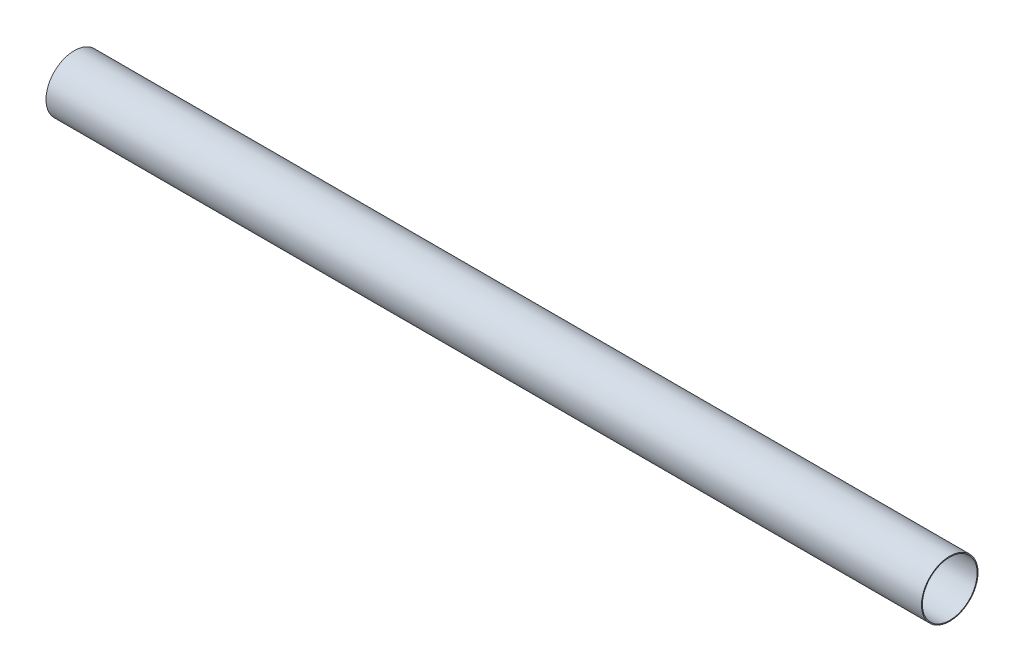
SolidWorks part; units mm, degrees
ref_plane "Front Plane" through (0, 0, 0) normal (0, 0, 1) x (1, 0, 0)
ref_plane "Top Plane" through (0, 0, 0) normal (0, 1, 0) x (1, 0, 0)
ref_plane "Right Plane" through (0, 0, 0) normal (1, 0, 0) x (0, 0, -1)
sketch "Sketch3" plane through (0, 0, 0) normal (1, 0, 0) x (0, 0, -1)
  circle A0 centre (0, 0) radius 76.2
extrude "Extrude-Thin1" add sketch "Sketch3" along normal blind 2438.4 thin
